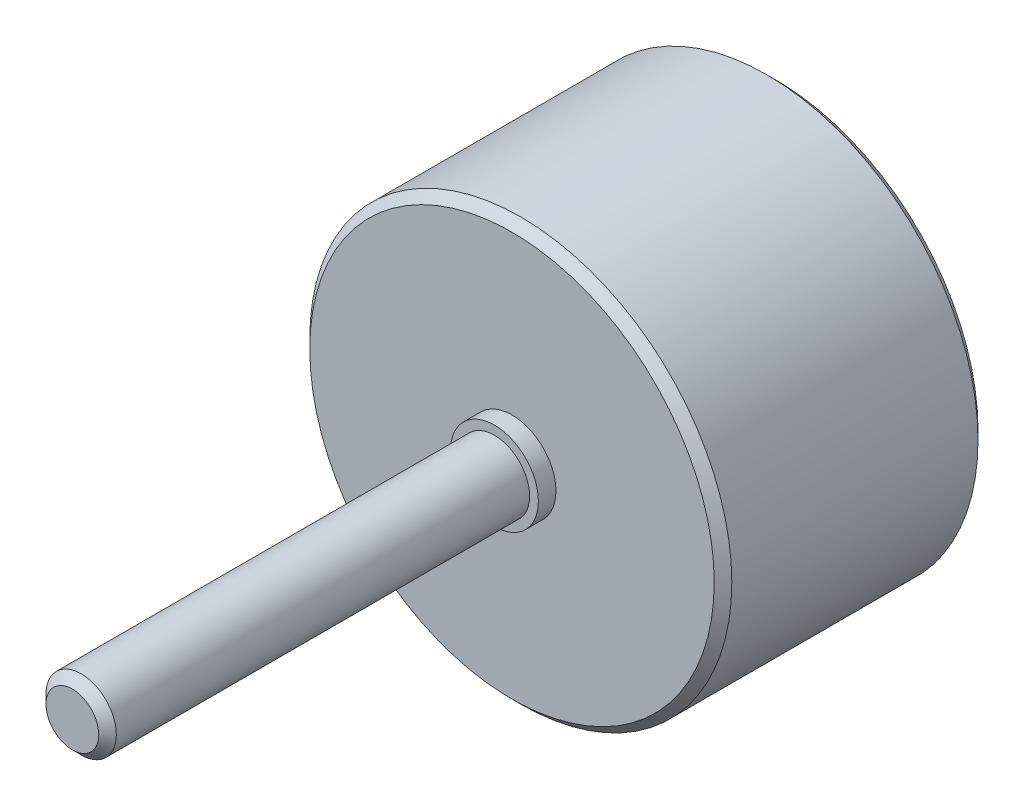
SolidWorks part; units mm, degrees
ref_plane "Plan de face" through (0, 0, 0) normal (0, 0, 1) x (1, 0, 0)
ref_plane "Plan de dessus" through (0, 0, 0) normal (0, 1, 0) x (1, 0, 0)
ref_plane "Plan de droite" through (0, 0, 0) normal (1, 0, 0) x (0, 0, -1)
sketch "Esquisse1" plane through (0, 0, 0) normal (0, 0, 1) x (1, 0, 0)
  circle A0 centre (0, 0) radius 24
  dimension "D1" = 48
extrude "Boss.-Extru.1" add sketch "Esquisse1" along normal blind 30
sketch "Esquisse2" plane through (0, 0, 30) normal (0, 0, 1) x (1, 0, 0)
  circle A0 centre (0, 0) radius 4
  dimension "D1" = 8
extrude "Boss.-Extru.2" add sketch "Esquisse2" along normal blind 50
sketch "Esquisse3" plane through (0, 0, 30) normal (0, 0, 1) x (1, 0, 0)
  circle A0 centre (0, 0) radius 5
  dimension "D1" = 10
extrude "Boss.-Extru.3" add sketch "Esquisse3" along normal blind 2
sketch "Esquisse4" plane through (0, 0, 0) normal (0, 0, -1) x (-1, 0, 0)
  circle A0 centre (0, 0) radius 3
  dimension "D1" = 6
extrude "Enlèv. mat.-Extru.1" cut sketch "Esquisse4" against normal blind 10
chamfer "Chanfrein1" distance 1 angle 45 3 edges at (24, 0, 0) (24, 0, 30) (4, 0, 80)
